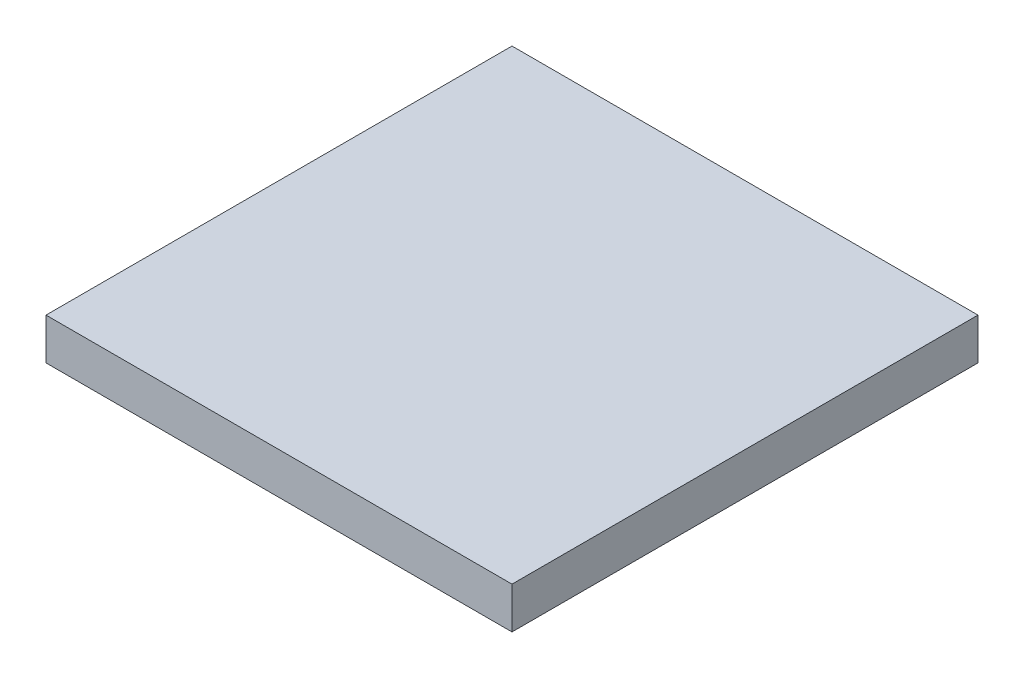
SolidWorks part; units mm, degrees
ref_plane "Front Plane" through (0, 0, 0) normal (0, 0, 1) x (1, 0, 0)
ref_plane "Top Plane" through (0, 0, 0) normal (0, 1, 0) x (1, 0, 0)
ref_plane "Right Plane" through (0, 0, 0) normal (1, 0, 0) x (0, 0, -1)
sketch "Sketch1" plane through (0, 0, 0) normal (0, 1, 0) x (1, 0, 0)
  line L1 (0, 0) -> (40, 0)
  line L2 (0, 0) -> (0, 40)
  line L3 (0, 40) -> (40, 40)
  line L4 (40, 0) -> (40, 40)
  dimension "D1" = 40
extrude "Boss-Extrude1" add sketch "Sketch1" along normal blind 3.556
